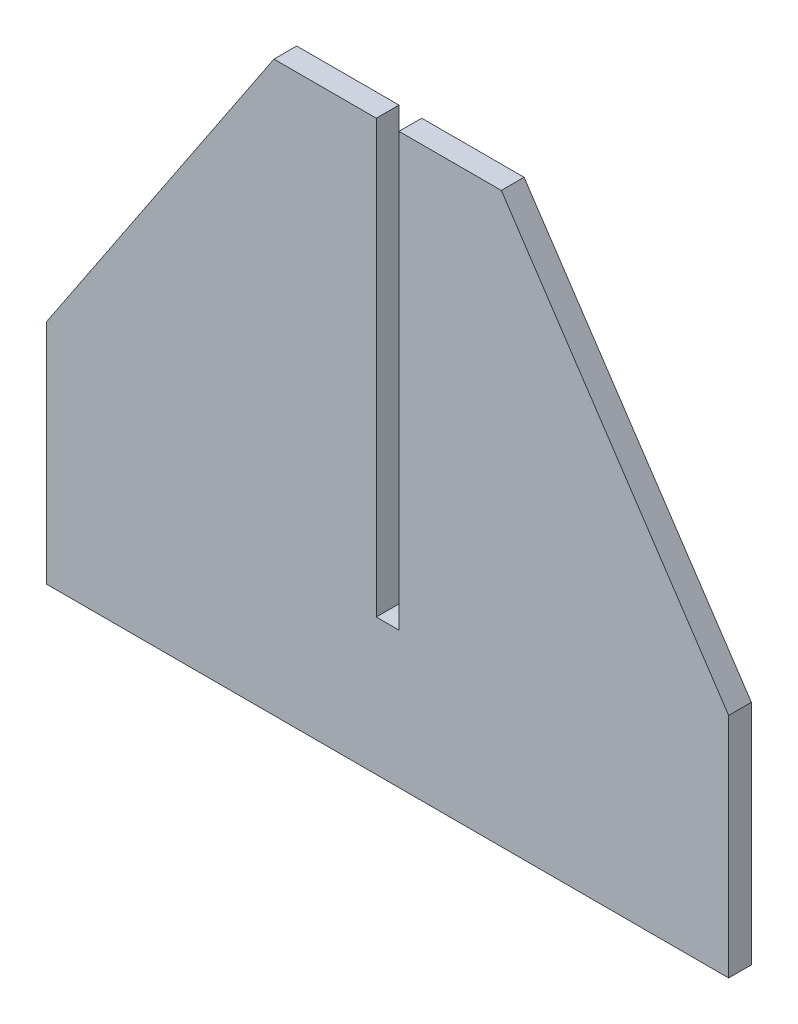
SolidWorks part; units mm, degrees
ref_plane "Front" through (0, 0, 0) normal (0, 0, 1) x (1, 0, 0)
ref_plane "Top" through (0, 0, 0) normal (0, 1, 0) x (1, 0, 0)
ref_plane "Right" through (0, 0, 0) normal (1, 0, 0) x (0, 0, -1)
sketch "Sketch1" plane through (0, 0, 0) normal (0, 0, 1) x (1, 0, 0)
  line L0 (0, 148.2143) -> (0, -160.7143) construction
  line L1 (150, -115) -> (-150, -115)
  line L2 (-150, -115) -> (-150, -15)
  line L3 (-150, -15) -> (-50, 135)
  line L5 (150, -15) -> (50, 135)
  line L6 (150, -115) -> (150, -15)
  line L7 (50, 135) -> (5, 135)
  line L8 (5, 135) -> (5, -55)
  line L9 (5, -55) -> (-5, -55)
  line L10 (-50, 135) -> (-5, 135)
  line L11 (-5, 135) -> (-5, -55)
  point P9 (0, 135)
  point P11 (0, -115)
  point P16 (0, -55)
  dimension "D1" = 250
  dimension "D2" = 150
  dimension "D3" = 100
  dimension "D4" = 50
  dimension "D5" = 115
  dimension "D6" = 5
  dimension "D7" = 190
extrude "Boss-Extrude1" add sketch "Sketch1" along normal blind 10
